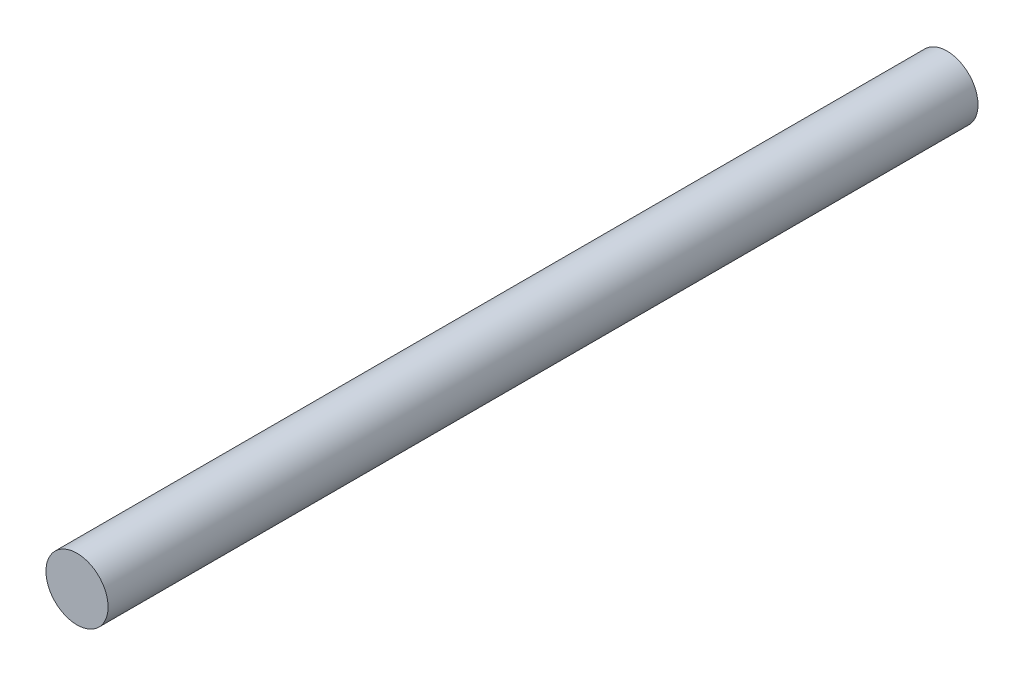
SolidWorks part; units mm, degrees
ref_plane "Plan de face" through (0, 0, 0) normal (0, 0, 1) x (1, 0, 0)
ref_plane "Plan de dessus" through (0, 0, 0) normal (0, 1, 0) x (1, 0, 0)
ref_plane "Plan de droite" through (0, 0, 0) normal (1, 0, 0) x (0, 0, -1)
sketch "Esquisse1" plane through (0, 0, 0) normal (0, 0, 1) x (1, 0, 0)
  circle A0 centre (0, 0) radius 2.5
  dimension "D1" = 5
extrude "Boss.-Extru.1" add sketch "Esquisse1" along normal blind 70
